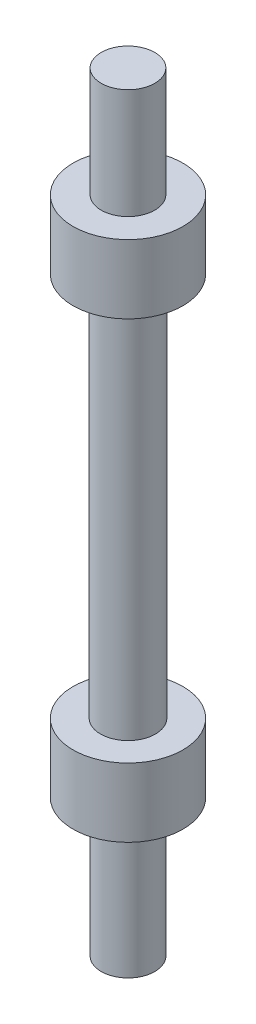
SolidWorks part; units mm, degrees
ref_plane "Front Plane" through (0, 0, 0) normal (0, 0, 1) x (1, 0, 0)
ref_plane "Top Plane" through (0, 0, 0) normal (0, 1, 0) x (1, 0, 0)
ref_plane "Right Plane" through (0, 0, 0) normal (1, 0, 0) x (0, 0, -1)
sketch "Sketch1" plane through (0, 0, 0) normal (0, 1, 0) x (1, 0, 0)
  circle A0 centre (0, 0) radius 2
  dimension "D1" = 4
extrude "Boss-Extrude1" add sketch "Sketch1" along normal blind 28
sketch "Sketch2" plane through (0, 0, 0) normal (0, -1, 0) x (1, 0, 0)
  circle A0 centre (0, 0) radius 4
  dimension "D1" = 8
extrude "Boss-Extrude2" add sketch "Sketch2" along normal blind 5 contours A0
sketch "Sketch3" plane through (0, -5, 0) normal (0, -1, 0) x (1, 0, 0)
  circle A0 centre (0, 0) radius 1.95
  dimension "D1" = 3.9
extrude "Boss-Extrude3" add sketch "Sketch3" along normal blind 10
sketch "Sketch7" plane through (0, 28, 0) normal (0, 1, 0) x (1, 0, 0)
  circle A0 centre (0, 0) radius 4
extrude "Boss-Extrude5" add sketch "Sketch7" along normal blind 5
sketch "Sketch8" plane through (0, 33, 0) normal (0, 1, 0) x (1, 0, 0)
  circle A0 centre (0, 0) radius 1.95
  dimension "D1" = 3.9
extrude "Boss-Extrude6" add sketch "Sketch8" along normal blind 8
